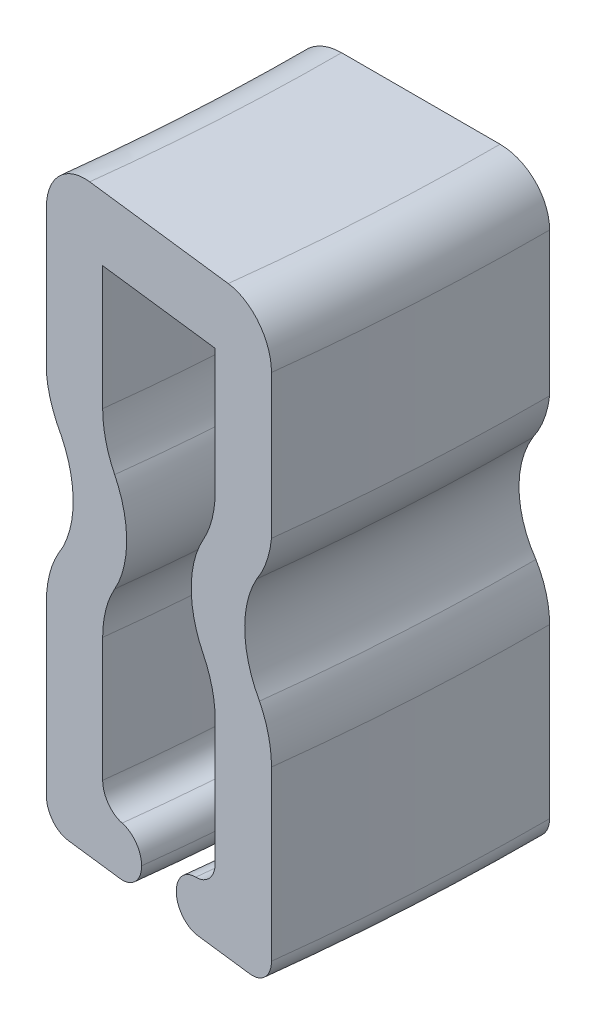
SolidWorks part; units mm, degrees
ref_plane "Front Plane" through (0, 0, 0) normal (0, 0, 1) x (1, 0, 0)
ref_plane "Top Plane" through (0, 0, 0) normal (0, 1, 0) x (1, 0, 0)
ref_plane "Right Plane" through (0, 0, 0) normal (1, 0, 0) x (0, 0, -1)
sketch "DualPropShadow" plane through (0, 0, 0) normal (0, 0, 1) x (1, 0, 0)
  line L0 (-1.2, 1.2) -> (0, 3.2)
  line L1 (-1.2, -1.2) -> (1.2, -1.2)
  line L2 (-1.2, -1.2) -> (-1.2, 1.2)
  line L3 (-1.2, 1.2) -> (1.2, 1.2) construction
  line L4 (1.2, -1.2) -> (1.2, 1.2)
  line L5 (-1.2, -1.2) -> (1.2, 1.2) construction
  line L6 (-1.2, 1.2) -> (1.2, -1.2) construction
  line L7 (0, 3.2) -> (1.2, 1.2)
  line L8 (0, 5.2) -> (0, 1.2) construction
  line L9 (-1000, 3.2) -> (49000, 3.2) construction
  line L10 (-1.2, 5.2) -> (1.2, 7.6) construction
  line L11 (-1.2, 7.6) -> (1.2, 5.2) construction
  line L12 (-1.2, 5.2) -> (1.2, 5.2) construction
  line L13 (0, 3.2) -> (1.2, 5.2)
  line L14 (1.2, 7.6) -> (1.2, 5.2)
  line L15 (-1.2, 7.6) -> (-1.2, 5.2)
  line L16 (-1.2, 7.6) -> (1.2, 7.6)
  line L17 (-1.2, 5.2) -> (0, 3.2)
  point P0 (0, 0)
  point P6 (1.2, 0)
  point P16 (0, 6.4)
  dimension "D1" = 2.4
  dimension "D2" = 4.4
  dimension "D3" = 2.4
sketch "Sketch2" plane through (0, 0, 0) normal (0, 0, 1) x (1, 0, 0)
  line L0 (-1.2, -1.2) -> (-1.2, 1.2) construction
  line L1 (-1.2, -1.2) -> (1.2, -1.2) construction
  line L2 (1.2, -1.2) -> (1.2, 1.2) construction
  line L3 (0, 3.2) -> (1.2, 1.2) construction
  line L4 (-1.2, 1.2) -> (0, 3.2) construction
  line L5 (1.2, 7.6) -> (1.2, 5.2) construction
  line L6 (0, 3.2) -> (1.2, 5.2) construction
  line L7 (-1.2, 5.2) -> (0, 3.2) construction
  line L8 (-1.2, 7.6) -> (-1.2, 5.2) construction
  line L9 (-1.2, 7.6) -> (1.2, 7.6) construction
  line L10 (-1.2, -1.2) -> (-1.2, 1.2) construction
  line L11 (-1.2, -1.2) -> (1.2, -1.2) construction
  line L12 (1.2, -1.2) -> (1.2, 1.2) construction
  line L13 (0, 3.2) -> (1.2, 1.2) construction
  line L14 (-1.2, 1.2) -> (0, 3.2) construction
  line L15 (1.2, 7.6) -> (1.2, 5.2) construction
  line L16 (0, 3.2) -> (1.2, 5.2) construction
  line L17 (-1.2, 5.2) -> (0, 3.2) construction
  line L18 (-1.2, 7.6) -> (-1.2, 5.2) construction
  line L19 (-1.2, 7.6) -> (1.2, 7.6) construction
  line L20 (0, -996.8) -> (0, 49003.2) construction
  line L21 (-1000, 3.2) -> (49000, 3.2) construction
  line L22 (-1.3, 7.7) -> (1.3, 7.7)
  line L23 (-1.2, 7.7) -> (-1.2, 7.6) construction
  line L24 (-1.3, 7.7) -> (-1.3, 5.2)
  line L25 (-1.3, -1.3) -> (-1.3, 1.2)
  line L26 (-1.2, 7.6) -> (-1.3, 7.6) construction
  line L27 (-0.746, 3.2) -> (-0.746, 4.4434) construction
  line L28 (-1.3, 5.2) -> (-1.3, 1.2) construction
  line L29 (-1.023, 4.2) -> (-0.423, 3.2) construction
  line L30 (1.6, 9) -> (-1.6, 9)
  line L31 (-1.3, 5.2) -> (-1.3, 1.2) construction
  line L32 (-1.3, -1.3) -> (1.3, -1.3) construction
  line L33 (1.3, 7.7) -> (1.3, 5.2) construction
  line L34 (-1.3, 7.7) -> (1.3, 7.7) construction
  line L35 (1.3, -1.3) -> (1.3, 1.2) construction
  line L36 (-2.6, 8) -> (-2.6, 5.1)
  line L37 (-1.3, 9) -> (-1.3, 7.7) construction
  line L38 (-1.3, 7.7) -> (-2.6, 7.7) construction
  line L39 (2.6, 8) -> (2.6, 5.1)
  line L40 (-0.4, -2.295) -> (-0.4, -1.2) construction
  line L41 (-1.2, 0) -> (-0.4, 0) construction
  line L42 (-0.4, 0) -> (0.4, 0) construction
  line L43 (0.4, 0) -> (1.2, 0) construction
  line L44 (-2.6, 1.1) -> (-2.6, -2.295)
  line L45 (-2.1, -2.795) -> (-0.9, -2.795)
  line L46 (1.3, 7.7) -> (1.3, 5.2)
  line L47 (1.3, 5.2) -> (1.3, 1.2) construction
  line L48 (2.1, -2.795) -> (0.9, -2.795)
  line L49 (1.3, -1.3) -> (1.3, 1.2)
  line L50 (2.6, 1.1) -> (2.6, -2.295)
  line L51 (-1.3, 8.35) -> (0, 8.35) construction
  arc A0 (-1.3, 5.2) -> (-1.023, 4.2) centre (0.6437, 5.2) ccw
  arc A1 (-1.023, 4.2) -> (-1.023, 2.2) centre (-2.6897, 3.2) cw
  arc A2 (-1.3, 1.2) -> (-1.023, 2.2) centre (0.6437, 1.2) cw
  arc A3 (-2.6, 5.1) -> (-2.2588, 4.2) centre (-0.6686, 5.3176) ccw
  arc A4 (-2.6, 1.1) -> (-2.323, 2.1) centre (-0.6563, 1.1) cw
  arc A5 (-2.2588, 4.2) -> (-2.323, 2.1) centre (-3.9254, 3.2) cw
  arc A6 (-2.6, 8) -> (-1.6, 9) centre (-1.6, 8) cw
  arc A7 (-1.3, -1.3) -> (-0.85, -1.7975) centre (-0.8, -1.3) ccw
  arc A8 (-0.85, -1.7975) -> (-0.4, -2.295) centre (-0.9, -2.295) cw
  arc A9 (-2.6, -2.295) -> (-2.1, -2.795) centre (-2.1, -2.295) ccw
  arc A10 (-0.4, -2.295) -> (-0.9, -2.795) centre (-0.9, -2.295) cw
  arc A11 (2.6, 8) -> (1.6, 9) centre (1.6, 8) ccw
  arc A12 (1.3, 5.2) -> (1.023, 4.2) centre (-0.6437, 5.2) cw
  arc A13 (2.6, -2.295) -> (2.1, -2.795) centre (2.1, -2.295) cw
  arc A14 (2.6, 5.1) -> (2.2588, 4.2) centre (0.6686, 5.3176) cw
  arc A15 (2.6, 1.1) -> (2.323, 2.1) centre (0.6563, 1.1) ccw
  arc A16 (2.2588, 4.2) -> (2.323, 2.1) centre (3.9254, 3.2) ccw
  arc A17 (1.3, 1.2) -> (1.023, 2.2) centre (-0.6437, 1.2) ccw
  arc A18 (1.023, 4.2) -> (1.023, 2.2) centre (2.6897, 3.2) ccw
  arc A19 (0.4, -2.295) -> (0.9, -2.795) centre (0.9, -2.295) ccw
  arc A20 (1.3, -1.3) -> (0.85, -1.7975) centre (0.8, -1.3) cw
  arc A21 (0.85, -1.7975) -> (0.4, -2.295) centre (0.9, -2.295) ccw
  point P60 (-1.2, 0)
  point P66 (0, 9)
  point P67 (0, 7.7)
  dimension "D3" = 1
  dimension "D4" = 0.5
  dimension "D2" = 1.3
  dimension "D1" = 0.1
sketch "Sketch12" plane through (0, 0, 0) normal (0, 1, 0) x (1, 0, 0)
  line L0 (-201000, 0) -> (249000, 0) construction
  arc A0 (0, 0) -> (-0.2976, -4.9911) centre (-42, 0) cw
  dimension "D1" = 42
  dimension "D2" = 5
sweep "Sweep2" add profiles "Sketch2" path "Sketch12"
equation "\"prop_height\"= 4.4mm"
equation "\"prop_th\"= 2.4mm"
equation "\"prop_indent_height\"= 2.4mm"
equation "\"prop_radius\"= 42mm"
equation "\"D1@DualPropShadow\" = \"prop_indent_height\""
equation "\"D2@DualPropShadow\" = \"prop_height\""
equation "\"D3@DualPropShadow\" = \"prop_th\""
equation "\"D1@Sketch12\"=\"prop_radius\""
